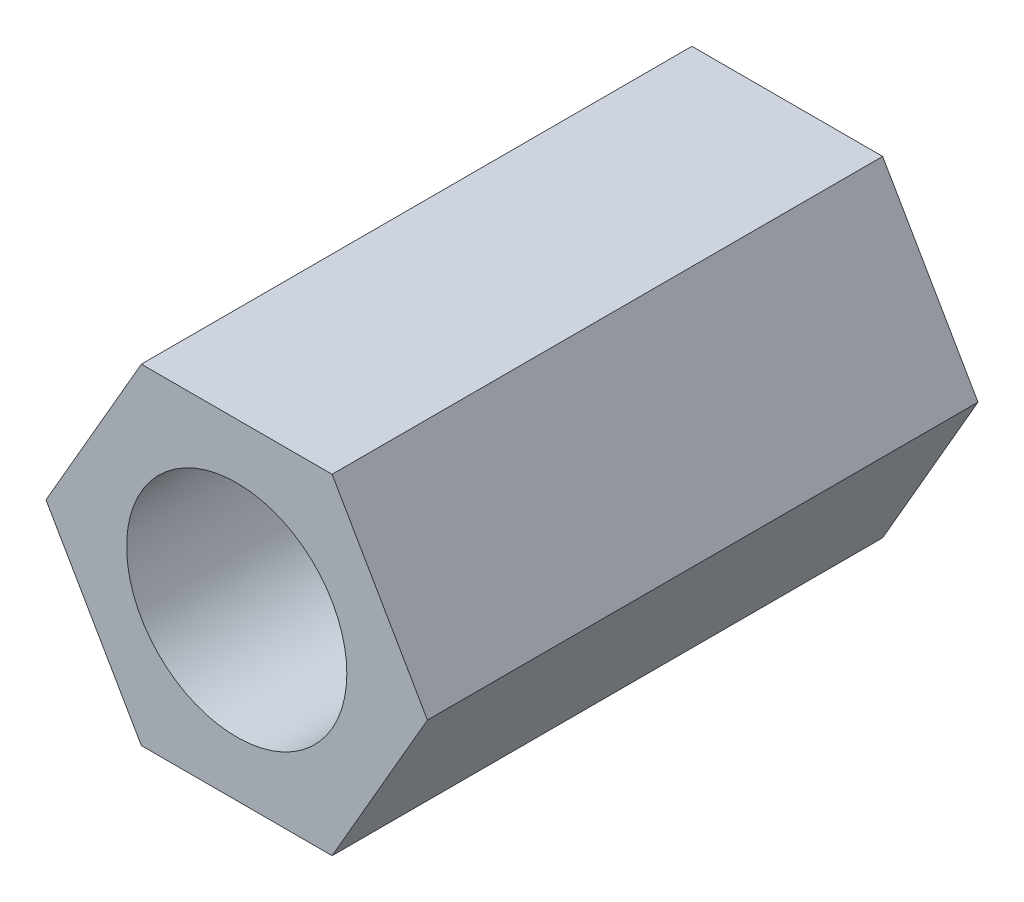
SolidWorks part; units mm, degrees
ref_plane "Plan de face" through (0, 0, 0) normal (0, 0, 1) x (1, 0, 0)
ref_plane "Plan de dessus" through (0, 0, 0) normal (0, 1, 0) x (1, 0, 0)
ref_plane "Plan de droite" through (0, 0, 0) normal (1, 0, 0) x (0, 0, -1)
sketch "Esquisse1" plane through (0, 0, 0) normal (0, 0, 1) x (1, 0, 0)
  line L1 (-3.4641, 0) -> (-1.7321, -3)
  line L2 (-1.7321, -3) -> (1.7321, -3)
  line L3 (1.7321, -3) -> (3.4641, 0)
  line L4 (3.4641, 0) -> (1.7321, 3)
  line L5 (1.7321, 3) -> (-1.7321, 3)
  line L6 (-1.7321, 3) -> (-3.4641, 0)
  circle A0 centre (0, 0) radius 2
  circle A1 centre (0, 0) radius 3 construction
  dimension "D1" = 4
  dimension "D2" = 6
extrude "Boss.-Extru.1" add sketch "Esquisse1" along normal blind 10
